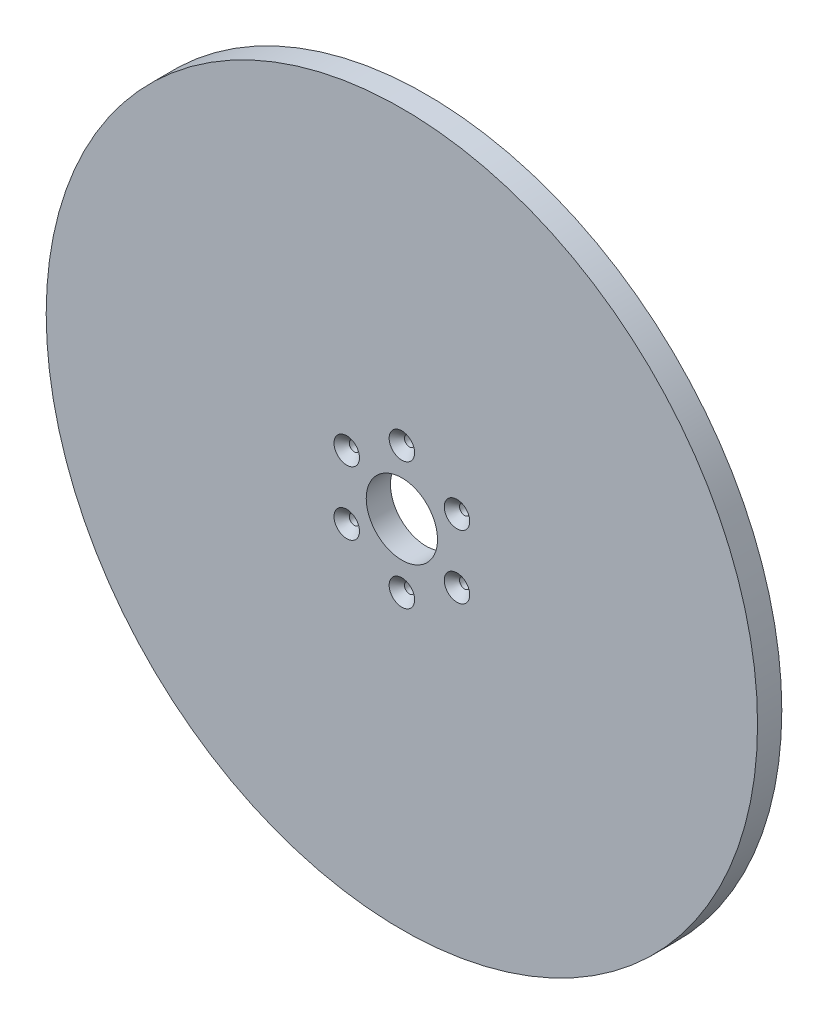
SolidWorks part; units mm, degrees
ref_plane "Front Plane" through (0, 0, 0) normal (0, 0, 1) x (1, 0, 0)
ref_plane "Top Plane" through (0, 0, 0) normal (0, 1, 0) x (1, 0, 0)
ref_plane "Right Plane" through (0, 0, 0) normal (1, 0, 0) x (0, 0, -1)
sketch "Sketch1" plane through (0, 0, 0) normal (0, 0, 1) x (1, 0, 0)
  circle A0 centre (0, 0) radius 139.7
  circle A1 centre (0, 0) radius 14
  dimension "D1" = 279.4
  dimension "D2" = 28
extrude "Boss-Extrude1" add sketch "Sketch1" along normal blind 9.525
sketch "Sketch2" plane through (0, 0, 9.525) normal (0, 0, 1) x (1, 0, 0)
  circle A0 centre (0, 25) radius 2
  dimension "D1" = 4
  dimension "D2" = 25
extrude "Cut-Extrude1" cut sketch "Sketch2" against normal through all
pattern_circular "CirPattern1" count 6 over 360 about axis through (0, 0, 0) along (0, 0, 1) of "Cut-Extrude1"
chamfer "Chamfer1" distance 3 angle 45 6 edges at (-20.6506, 14.2321, 9.525) (-22.6506, -10.7679, 9.525) (-2, -25, 9.525) (20.6506, -14.2321, 9.525) (22.6506, 10.7679, 9.525) (2, 25, 9.525)
